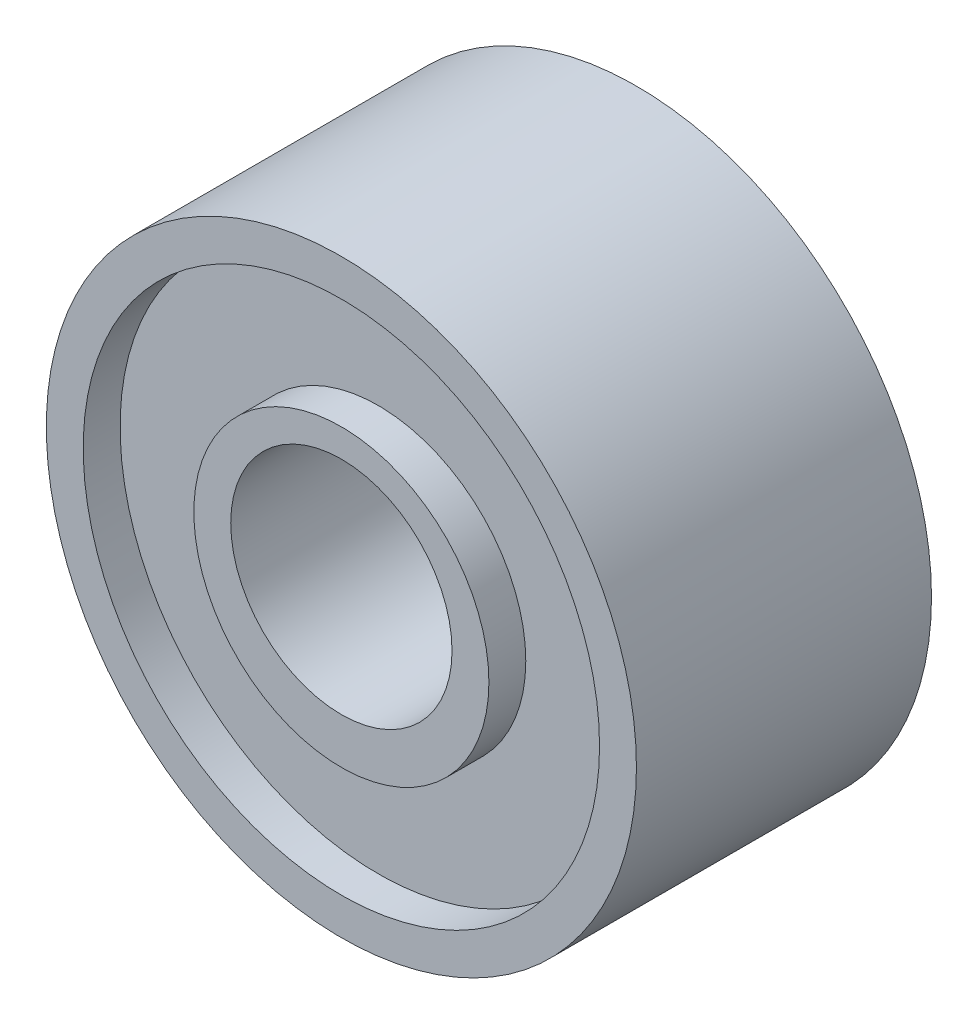
SolidWorks part; units mm, degrees
ref_plane "Front Plane" through (0, 0, 0) normal (0, 0, 1) x (1, 0, 0)
ref_plane "Top Plane" through (0, 0, 0) normal (0, 1, 0) x (1, 0, 0)
ref_plane "Right Plane" through (0, 0, 0) normal (1, 0, 0) x (0, 0, -1)
sketch "Sketch1" plane through (0, 0, 0) normal (0, 0, 1) x (1, 0, 0)
  circle A0 centre (0, 0) radius 4
  circle A1 centre (0, 0.1202) radius 1.5
  dimension "D1" = 3
  dimension "D2" = 8
extrude "Boss-Extrude2" add sketch "Sketch1" along normal blind 4
sketch "Sketch3" plane through (0, 0, 4) normal (0, 0, 1) x (1, 0, 0)
  circle A0 centre (0, 0) radius 2
  circle A1 centre (0, 0) radius 3.5
  dimension "D1" = 4
  dimension "D2" = 7
extrude "Cut-Extrude1" cut sketch "Sketch3" against normal blind 0.5
sketch "Sketch4" plane through (0, 0, 0) normal (0, 0, -1) x (-1, 0, 0)
  circle A0 centre (0, 0) radius 2
  circle A1 centre (0, 0) radius 3.5
  dimension "D1" = 4
  dimension "D2" = 7
extrude "Cut-Extrude2" cut sketch "Sketch4" against normal blind 0.5
